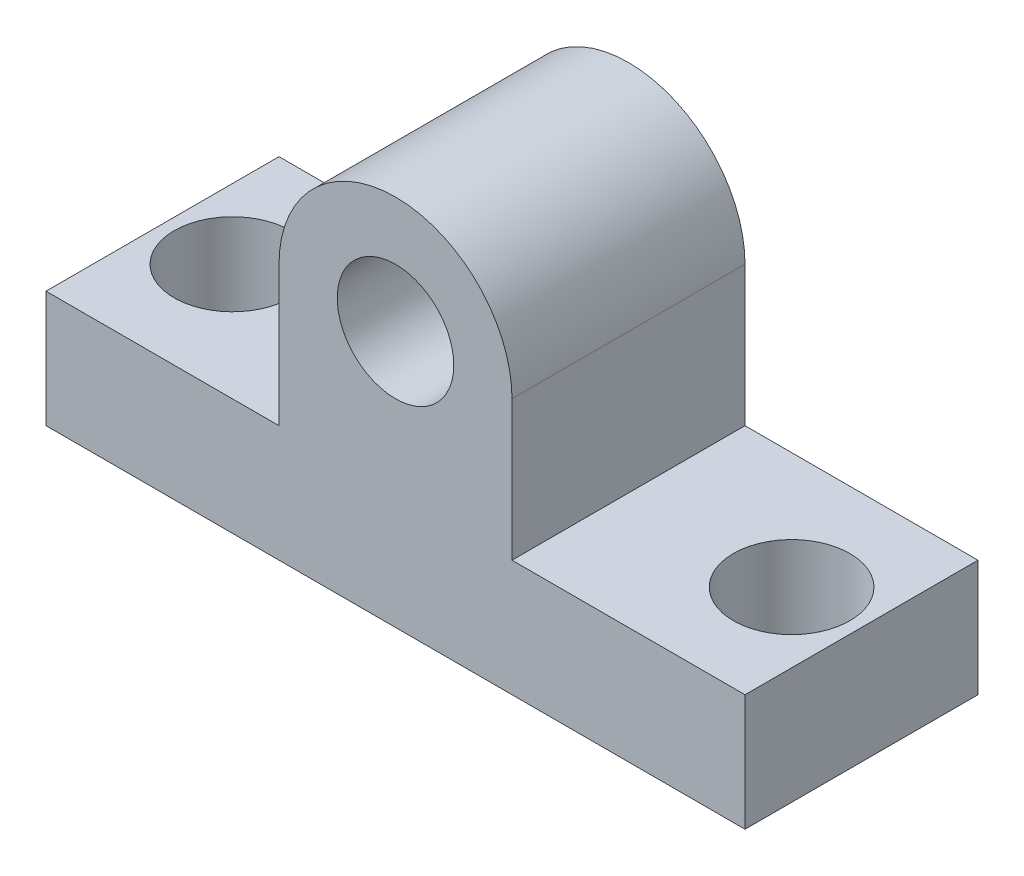
SolidWorks part; units mm, degrees
ref_plane "前视基准面" through (0, 0, 0) normal (0, 0, 1) x (1, 0, 0)
ref_plane "上视基准面" through (0, 0, 0) normal (0, 1, 0) x (1, 0, 0)
ref_plane "右视基准面" through (0, 0, 0) normal (1, 0, 0) x (0, 0, -1)
sketch "草图1" plane through (0, 0, 0) normal (0, 0, 1) x (1, 0, 0)
  line L0 (5, 0) -> (15, 0)
  line L1 (15, 0) -> (15, -5)
  line L2 (15, -5) -> (-15, -5)
  line L4 (5, 6) -> (5, 0)
  line L5 (-15, 0) -> (-15, -5)
  line L6 (-5, 0) -> (-15, 0)
  line L7 (-5, 6) -> (-5, 0)
  arc A0 (5, 6) -> (-5, 6) centre (0, 6) ccw
  circle A1 centre (0, 6) radius 2.5
  point P11 (0, -5)
  dimension "D3" = 10
  dimension "D4" = 5
  dimension "D1" = 6
  dimension "D2" = 5
extrude "凸台-拉伸1" add sketch "草图1" along normal blind 10
sketch "草图2" plane through (0, 0, 0) normal (0, 1, 0) x (1, 0, 0)
  line L0 (-5, 0) -> (-15, 0) construction
  line L4 (-15, -10) -> (-15, 0) construction
  circle A0 centre (-12, -5) radius 2.5
  dimension "D1" = 5
  dimension "D2" = 3
extrude "切除-拉伸1" cut sketch "草图2" against normal blind 5 contours A0
sketch "草图3" plane through (0, 0, 0) normal (0, 1, 0) x (1, 0, 0)
  line L0 (15, -10) -> (15, 0) construction
  line L1 (15, -10) -> (5, -10) construction
  circle A0 centre (12, -5) radius 2.5
  dimension "D1" = 3
  dimension "D2" = 5
  dimension "D3" = 5
extrude "切除-拉伸2" cut sketch "草图3" against normal blind 5 contours A0
